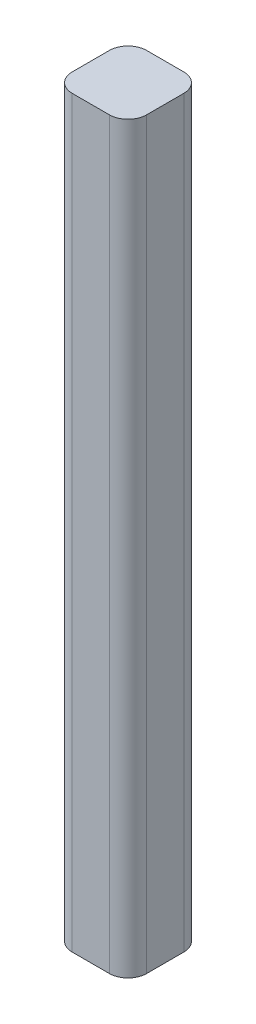
SolidWorks part; units mm, degrees
ref_plane "Plano frontal" through (0, 0, 0) normal (0, 0, 1) x (1, 0, 0)
ref_plane "Plano superior" through (0, 0, 0) normal (0, 1, 0) x (1, 0, 0)
ref_plane "Plano direito" through (0, 0, 0) normal (1, 0, 0) x (0, 0, -1)
sketch "Esboço1" plane through (0, 0, 0) normal (0, 1, 0) x (1, 0, 0)
  line L1 (-2, -4) -> (2, -4)
  line L2 (-4, -2) -> (-4, 2)
  line L3 (-2, 4) -> (2, 4)
  line L4 (4, -2) -> (4, 2)
  line L5 (-4, -4) -> (4, 4) construction
  line L6 (-4, 4) -> (4, -4) construction
  arc A0 (2, 4) -> (4, 2) centre (2, 2) cw
  arc A1 (4, -2) -> (2, -4) centre (2, -2) cw
  arc A2 (-2, -4) -> (-4, -2) centre (-2, -2) cw
  arc A3 (-4, 2) -> (-2, 4) centre (-2, 2) cw
  point P0 (0, 0)
  dimension "D3" = 2
  dimension "D1" = 8
  dimension "D2" = 8
extrude "Ressalto-extrusão1" add sketch "Esboço1" along normal blind 80
